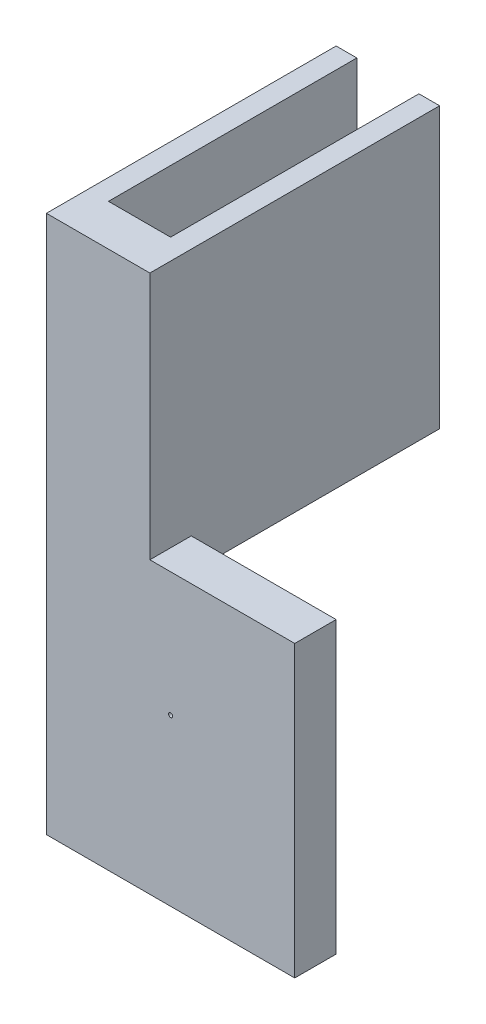
SolidWorks part; units mm, degrees
ref_plane "Plan de face" through (0, 0, 0) normal (0, 0, 1) x (1, 0, 0)
ref_plane "Plan de dessus" through (0, 0, 0) normal (0, 1, 0) x (1, 0, 0)
ref_plane "Plan de droite" through (0, 0, 0) normal (1, 0, 0) x (0, 0, -1)
sketch "Esquisse1" plane through (0, 0, 0) normal (0, 0, 1) x (1, 0, 0)
  line L1 (-34.3168, 32.8543) -> (25.6832, 32.8543)
  line L2 (-34.3168, 32.8543) -> (-34.3168, -37.1457)
  line L3 (-34.3168, -37.1457) -> (25.6832, -37.1457)
  line L4 (25.6832, 32.8543) -> (25.6832, -37.1457)
  dimension "D1" = 60
  dimension "D2" = 70
extrude "Extrusion1" add sketch "Esquisse1" along normal blind 10
sketch "Esquisse2" plane through (0, 0, 0) normal (0, 0, -1) x (-1, 0, 0)
  line L0 (-25.6832, 32.8543) -> (34.3168, 32.8543) construction
  line L1 (34.3168, 32.8543) -> (34.3168, -37.1457) construction
  circle A0 centre (4.3168, 2.8543) radius 0.5
  dimension "D3" = 1
  dimension "D1" = 30
  dimension "D2" = 30
extrude "Extrusion2" cut sketch "Esquisse2" against normal up to next
sketch "Esquisse3" plane through (0, 0, 10) normal (0, 0, 1) x (1, 0, 0)
  circle A0 centre (-4.3168, 2.8543) radius 23
  dimension "D1" = 46
sketch "Esquisse4" plane through (0, 32.8543, 0) normal (0, 1, 0) x (1, 0, 0)
  line L0 (25.6832, 0) -> (-34.3168, 0) construction
  line L1 (-34.3168, 0) -> (-9.3168, 0)
  line L2 (-34.3168, 0) -> (-34.3168, -10)
  line L3 (-34.3168, -10) -> (-9.3168, -10)
  line L4 (-9.3168, 0) -> (-9.3168, -10)
  line L5 (-27.3168, -10) -> (18.6832, -10) construction
  dimension "D1" = 25
extrude "Extrusion3" add sketch "Esquisse4" along normal blind 60
sketch "Esquisse5" plane through (0, 0, 0) normal (0, 0, -1) x (-1, 0, 0)
  line L0 (29.3168, 25.271) -> (24.9599, 12.9966)
  line L1 (9.3168, 92.8543) -> (14.3168, 92.8543)
  line L2 (9.3168, 92.8543) -> (9.3168, 25.271)
  line L3 (9.3168, 25.271) -> (14.3168, 23.5667)
  line L4 (14.3168, 92.8543) -> (14.3168, 23.5667)
  line L5 (34.3168, 92.8543) -> (29.3168, 92.8543)
  line L6 (34.3168, 92.8543) -> (34.3168, 25.271)
  line L7 (24.9599, 12.9966) -> (29.4003, 11.4204)
  line L8 (29.3168, 92.8543) -> (29.3168, 25.271)
  line L9 (29.4003, 11.4204) -> (34.3168, 25.271)
  line L10 (14.3168, 23.5667) -> (24.9599, 12.9966) construction
  circle A1 centre (4.3168, 2.8543) radius 23 construction
  dimension "D1" = 5
  dimension "D2" = 5
  dimension "D3" = 25
  dimension "D4" = 15
extrude "Extrusion4" add sketch "Esquisse5" along normal blind 60
